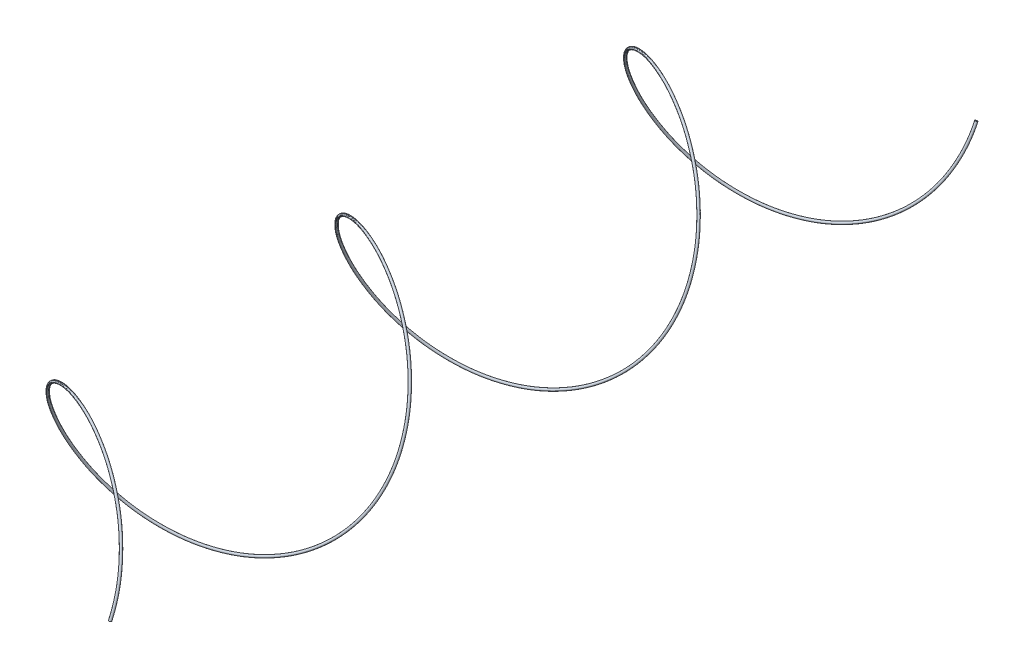
SolidWorks part; units mm, degrees
ref_plane "Front Plane" through (0, 0, 0) normal (0, 0, 1) x (1, 0, 0)
ref_plane "Top Plane" through (0, 0, 0) normal (0, 1, 0) x (1, 0, 0)
ref_plane "Right Plane" through (0, 0, 0) normal (1, 0, 0) x (0, 0, -1)
sketch "Sketch3" plane through (0, 0, 0) normal (0, 0, 1) x (1, 0, 0)
  circle A0 centre (0, 0) radius 4
  dimension "D1" = 8
curve "Helix/Spiral1" pitch 11.6667 height 35 turns 3
ref_plane "Plane1" through (4, 0, 0) normal (0, -0.907, 0.421) x (-1, 0, 0)
sketch "Sketch4" plane through (4, 0, 0) normal (0, -0.907, 0.421) x (-1, 0, 0)
  circle A0 centre (0.047, 0) radius 0.05
  dimension "D1" = 0.1
sweep "Sweep1" add profiles "Sketch4" path "Helix/Spiral1"
